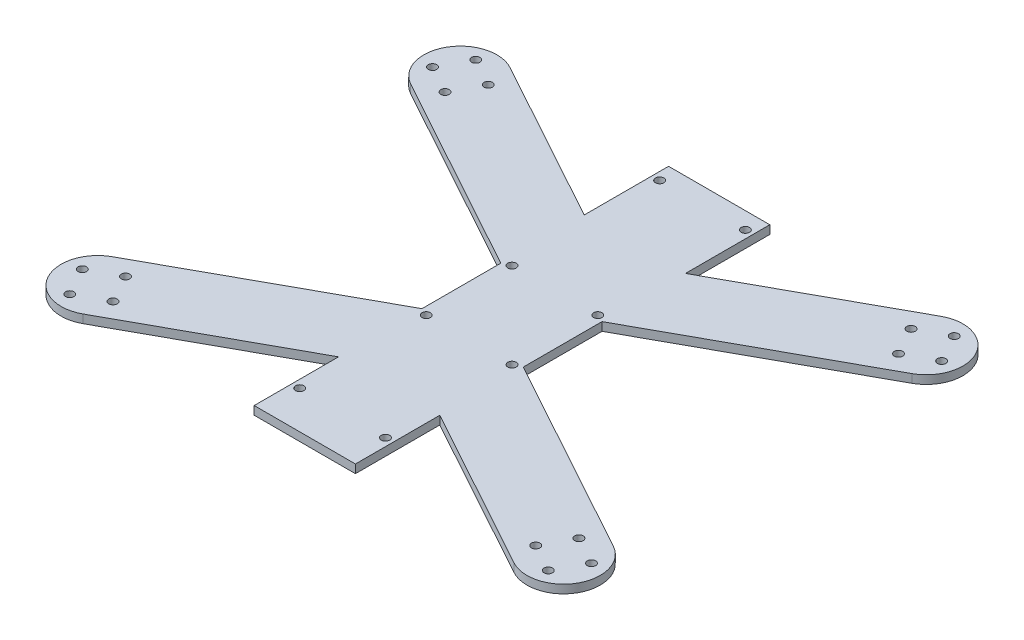
SolidWorks part; units mm, degrees
ref_plane "Front Plane" through (0, 0, 0) normal (0, 0, 1) x (1, 0, 0)
ref_plane "Top Plane" through (0, 0, 0) normal (0, 1, 0) x (1, 0, 0)
ref_plane "Right Plane" through (0, 0, 0) normal (1, 0, 0) x (0, 0, -1)
sketch "Sketch1" plane through (0, 0, 0) normal (0, 1, 0) x (1, 0, 0)
  line L0 (0, 64.5) -> (0, -15.25) construction
  line L1 (82.8538, 64.5) -> (-82.8538, 64.5) construction
  line L2 (82.8538, 64.5) -> (82.8538, -64.5) construction
  line L3 (82.8538, -64.5) -> (-82.8538, -64.5) construction
  line L4 (-82.8538, 64.5) -> (-82.8538, -64.5) construction
  line L5 (82.8538, 64.5) -> (-82.8538, -64.5) construction
  line L6 (82.8538, -64.5) -> (-82.8538, 64.5) construction
  line L7 (-82.8538, 0) -> (82.8538, 0) construction
  line L8 (-89.1164, 53.1079) -> (-18, 14.0126)
  line L9 (-15.25, 15.25) -> (15.25, 15.25) construction
  line L10 (-15.25, 15.25) -> (-15.25, -15.25) construction
  line L11 (-15.25, -15.25) -> (15.25, -15.25) construction
  line L12 (15.25, 15.25) -> (15.25, -15.25) construction
  line L13 (-15.25, 15.25) -> (15.25, -15.25) construction
  line L14 (-15.25, -15.25) -> (15.25, 15.25) construction
  line L15 (18, 73.6824) -> (-18, 73.6824)
  line L16 (18, 73.6824) -> (18, 43.6824)
  line L17 (18, -73.6824) -> (-18, -73.6824)
  line L18 (-18, 73.6824) -> (-18, 43.6824)
  line L19 (-76.5911, 75.8921) -> (-18, 43.6824)
  line L20 (-18, 14.0126) -> (-18, -14.0126)
  line L21 (76.5911, 75.8921) -> (18, 43.6824)
  line L22 (18, 73.6824) -> (18, 43.6824)
  line L23 (89.1164, 53.1079) -> (18, 14.0126)
  line L24 (18, 14.0126) -> (18, -14.0126)
  line L25 (-15.25, -15.25) -> (15.25, -15.25) construction
  line L26 (82.8538, -64.5) -> (-82.8538, -64.5) construction
  line L27 (89.1164, -53.1079) -> (18, -14.0126)
  line L29 (76.5911, -75.8921) -> (18, -43.6824)
  line L30 (-76.5911, -75.8921) -> (-18, -43.6824)
  line L31 (-18, -43.6824) -> (-18, -73.6824)
  line L33 (18, -43.6824) -> (18, -73.6824)
  line L34 (-89.1164, -53.1079) -> (-18, -14.0126)
  arc A1 (-76.5911, 75.8921) -> (-89.1164, 53.1079) centre (-82.8538, 64.5) ccw
  circle A2 centre (-15.25, 15.25) radius 1.5
  circle A3 centre (-15.25, 67.75) radius 1.5
  circle A4 centre (-15.25, -60.25) radius 1.5
  circle A5 centre (15.25, 67.75) radius 1.5
  circle A6 centre (15.25, 15.25) radius 1.5
  arc A7 (76.5911, 75.8921) -> (89.1164, 53.1079) centre (82.8538, 64.5) cw
  arc A8 (76.5911, -75.8921) -> (89.1164, -53.1079) centre (82.8538, -64.5) ccw
  circle A9 centre (15.25, -15.25) radius 1.5
  circle A12 centre (-15.25, -15.25) radius 1.5
  arc A13 (-76.5911, -75.8921) -> (-89.1164, -53.1079) centre (-82.8538, -64.5) cw
  circle A14 centre (15.25, -60.25) radius 1.5
  point P0 (0, 0)
  point P10 (0, 0)
  point P17 (0, 24.625)
  point P30 (0, 73.6824)
  dimension "D4" = 26
  dimension "D5" = 3
  dimension "D7" = 3
  dimension "D9" = 3
  dimension "D1" = 210
  dimension "D2" = 129
  dimension "D3" = 30.5
  dimension "D6" = 36
  dimension "D8" = 52.5
  dimension "D10" = 45
  dimension "D11" = 26
  dimension "D12" = 30
  dimension "D13" = 30
extrude "Boss-Extrude1" add sketch "Sketch1" along normal blind 3
sketch "Sketch2" plane through (0, 3, 0) normal (0, 1, 0) x (1, 0, 0)
  line L1 (-85.0858, 72.1823) -> (-75.1715, 66.732) construction
  line L2 (-76.5911, 75.8921) -> (-18, 43.6824) construction
  line L3 (-82.8538, 64.5) -> (-75.8433, 60.6461) construction
  line L4 (-90.5361, 62.268) -> (-85.0858, 72.1823) construction
  circle A0 centre (-82.8538, 64.5) radius 8 construction
  circle A1 centre (-85.0858, 72.1823) radius 1.5
  circle A2 centre (-75.1715, 66.732) radius 1.5
  circle A3 centre (-80.6218, 56.8177) radius 1.5
  circle A4 centre (-90.5361, 62.268) radius 1.5
  dimension "D1" = 16
  dimension "D2" = 3
extrude "Cut-Extrude1" cut sketch "Sketch2" against normal through all
mirror "Mirror1" about plane through (0, 0, 0) normal (0, 0, 1) of "Cut-Extrude1"
mirror "Mirror2" about plane through (0, 0, 0) normal (1, 0, 0) of "Mirror1", "Cut-Extrude1"
